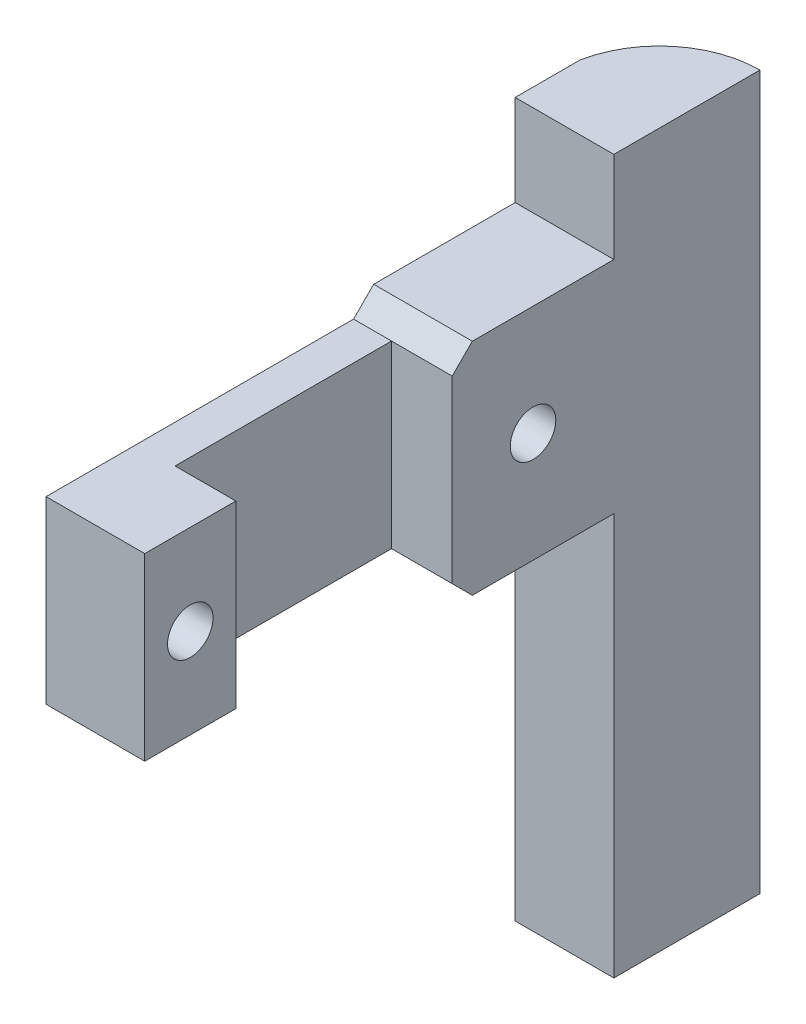
SolidWorks part; units mm, degrees
material "ABS"
ref_plane "Front" through (0, 0, 0) normal (0, 0, 1) x (1, 0, 0)
ref_plane "Top" through (0, 0, 0) normal (0, 1, 0) x (1, 0, 0)
ref_plane "Right" through (0, 0, 0) normal (1, 0, 0) x (0, 0, -1)
sketch "Sketch1" plane through (0, 0, 0) normal (1, 0, 0) x (0, 0, -1)
  line L1 (10.65, 14.5) -> (-10.65, 14.5)
  line L2 (10.65, 14.5) -> (10.65, -14.5)
  line L3 (10.65, -14.5) -> (-10.65, -14.5)
  line L4 (-10.65, 14.5) -> (-10.65, -14.5)
  line L5 (10.65, 14.5) -> (-10.65, -14.5) construction
  line L6 (10.65, -14.5) -> (-10.65, 14.5) construction
  point P0 (0, 0)
  dimension "D1" = 21.3
  dimension "D2" = 29
extrude "Boss-Extrude1" add sketch "Sketch1" along normal blind 25.87
sketch "Sketch3" plane through (25.87, 0, 0) normal (1, 0, 0) x (0, 0, -1)
  line L0 (-7.9983, 14.5) -> (-10.65, 11.8483)
  line L1 (-10.65, 11.8483) -> (-10.65, 14.5)
  line L2 (-10.65, 14.5) -> (-7.9983, 14.5)
  line L3 (-12.9395, 0) -> (4.891, 0)
  line L4 (10.65, 14.5) -> (-10.65, 14.5) construction
  line L5 (-10.65, 14.5) -> (-10.65, -14.5) construction
  line L6 (-10.65, -11.8483) -> (-10.65, -14.5)
  line L7 (-7.9983, -14.5) -> (-10.65, -11.8483)
  line L8 (-10.65, -14.5) -> (-7.9983, -14.5)
  line M6 (-10.65, 14.5) -> (-10.65, -14.5)
  line M7 (-10.65, -14.5) -> (10.65, -14.5)
  dimension "D1" = 0
  dimension "D2" = 45
  dimension "D3" = 3.75
  dimension "D4" = 17.8305
  dimension "D5" = 14.5
  dimension "D6" = 2.2895
extrude "Cut-Extrude1" cut sketch "Sketch3" against normal through all contours L7 M7 M6 | L1 L2 L0
sketch "Sketch5" plane through (0, 0, 10.65) normal (0, 0, 1) x (1, 0, 0)
  line L0 (25.87, 11.8483) -> (25.87, -11.8483) construction
  line L1 (25.87, 11.8483) -> (20.87, 11.8483)
  line L2 (25.87, 11.8483) -> (25.87, -11.8517)
  line L3 (25.87, -11.8517) -> (20.87, -11.8517)
  line L4 (20.87, 11.8483) -> (20.87, -11.8517)
  line L5 (25.87, 11.8483) -> (20.87, -11.8517) construction
  line L6 (25.87, -11.8517) -> (20.87, 11.8483) construction
  line L7 (5, 11.8483) -> (0, 11.8483)
  line L8 (5, 11.8483) -> (5, -11.8517)
  line L9 (5, -11.8517) -> (0, -11.8517)
  line L10 (0, 11.8483) -> (0, -11.8517)
  line L11 (5, 11.8483) -> (0, -11.8517) construction
  line L12 (5, -11.8517) -> (0, 11.8483) construction
  line L13 (0, 11.8483) -> (25.87, 11.8483) construction
  line L14 (0, 11.8483) -> (0, -11.8483) construction
  point P0 (23.37, -0.0017)
  point P5 (2.5, -0.0017)
  dimension "D1" = 0
  dimension "D2" = 5
  dimension "D3" = 0
  dimension "D4" = 23.7
  dimension "D5" = 0
  dimension "D6" = 0
  dimension "D7" = 5
  dimension "D8" = 23.7
extrude "Boss-Extrude2" add sketch "Sketch5" along normal blind 31.52
sketch "Sketch6" plane through (20.87, 0, 0) normal (-1, 0, 0) x (0, 0, 1)
  line L0 (42.17, 11.8483) -> (10.65, 11.8483) construction
  line L1 (42.17, 11.8483) -> (37.17, 11.8483)
  line L2 (42.17, 11.8483) -> (42.17, -11.8517)
  line L3 (42.17, -11.8517) -> (37.17, -11.8517)
  line L4 (37.17, 11.8483) -> (37.17, -11.8517)
  line L5 (42.17, 11.8483) -> (37.17, -11.8517) construction
  line L6 (42.17, -11.8517) -> (37.17, 11.8483) construction
  line L7 (42.17, 11.8483) -> (42.17, -11.8517) construction
  point P0 (39.67, -0.0017)
  point P5 (39.67, 11.8483)
  dimension "D1" = 0
  dimension "D2" = 0
  dimension "D3" = 5
  dimension "D4" = 23.7
extrude "Boss-Extrude3" add sketch "Sketch6" along normal blind 15.9
sketch "Sketch7" plane through (0, 0, -10.65) normal (0, 0, -1) x (-1, 0, 0)
  line L0 (-25.87, 14.5) -> (0, 14.5) construction
  line L1 (0, 26.5) -> (-25.87, 26.5)
  line L2 (0, 26.5) -> (0, -67.5)
  line L3 (0, -67.5) -> (-25.87, -67.5)
  line L4 (-25.87, 26.5) -> (-25.87, -67.5)
  line L5 (0, 26.5) -> (-25.87, -67.5) construction
  line L6 (0, -67.5) -> (-25.87, 26.5) construction
  line L7 (-25.87, -14.5) -> (0, -14.5) construction
  line L8 (0, -14.5) -> (0, 14.5) construction
  line L9 (-25.87, -14.5) -> (-25.87, 14.5) construction
  point P0 (-12.935, -20.5)
  point P5 (-12.935, 26.5)
  dimension "D1" = 12
  dimension "D2" = 53
  dimension "D3" = 0
  dimension "D4" = 0
extrude "Boss-Extrude4" add sketch "Sketch7" along normal blind 20
sketch "Sketch9" plane through (0, -67.5, 0) normal (0, -1, 0) x (-1, 0, 0)
  line L0 (-25.87, 10.65) -> (0, 10.65) construction
  line L1 (-25.87, 30.65) -> (-25.87, 10.65) construction
  line L2 (0.38, 16.65) -> (-26.12, 16.65)
  line L3 (-26.12, 16.65) -> (-26.12, 30.65)
  line L4 (-26.12, 30.65) -> (0.38, 30.65)
  line L5 (0.38, 30.65) -> (0.38, 16.65)
  circle A0 centre (-12.87, 16.65) radius 13.25
  line M5 (0, 10.65) -> (0, 30.65)
  line M6 (0, 30.65) -> (-25.87, 30.65)
  dimension "D1" = 6
  dimension "D2" = 13
  dimension "D3" = 26.5
  dimension "D4" = 14
  dimension "D5" = 26.5
  dimension "D6" = 90
extrude "Cut-Extrude2" cut sketch "Sketch9" against normal through all contours A0 L3 M5 M6
sketch "Sketch10" plane through (0, 0, 42.17) normal (0, 0, 1) x (1, 0, 0)
  line L1 (25.87, 11.8483) -> (0, 11.8483)
  line L2 (25.87, 11.8483) -> (25.87, -11.8517)
  line L3 (25.87, -11.8517) -> (0, -11.8517)
  line L4 (0, 11.8483) -> (0, -11.8517)
  dimension "D1" = 25.87
  dimension "D2" = 23.7
extrude "Boss-Extrude5" add sketch "Sketch10" along normal blind 9
sketch "Sketch13" plane through (0, 0, 51.17) normal (0, 0, 1) x (1, 0, 0)
  line L0 (0, 11.8483) -> (0, -11.8517) construction
  line L1 (12.87, 69.9983) -> (-12.87, 69.9983)
  line L2 (12.87, 69.9983) -> (12.87, -70.0017)
  line L3 (12.87, -70.0017) -> (-12.87, -70.0017)
  line L4 (-12.87, 69.9983) -> (-12.87, -70.0017)
  line L5 (12.87, 69.9983) -> (-12.87, -70.0017) construction
  line L6 (12.87, -70.0017) -> (-12.87, 69.9983) construction
  point P0 (0, -0.0017)
  dimension "D1" = 70
  dimension "D2" = 12.87
extrude "Cut-Extrude3" cut sketch "Sketch13" against normal through all
mirror "Mirror2" about plane through (12.87, 69.9983, -29.9) normal (1, 0, 0) of "Cut-Extrude3", "Cut-Extrude1", "Boss-Extrude2", "Boss-Extrude5", "Cut-Extrude2", "Boss-Extrude1", "Boss-Extrude4"
sketch "Sketch14" plane through (4.87, 0, 0) normal (1, 0, 0) x (0, 0, -1)
  line L0 (-42.17, 11.8483) -> (-10.65, 11.8483) construction
  line L1 (-46.17, 11.8483) -> (-39.17, 11.8483)
  line L2 (-46.17, 11.8483) -> (-46.17, -11.8517)
  line L3 (-46.17, -11.8517) -> (-39.17, -11.8517)
  line L4 (-39.17, 11.8483) -> (-39.17, -11.8517)
  line L6 (-10.65, 11.8483) -> (-10.65, -11.8483) construction
  dimension "D1" = 7
  dimension "D2" = 23.7
  dimension "D3" = 0
  dimension "D4" = 35.52
extrude "Boss-Extrude6" add sketch "Sketch14" along normal blind 8
hole_wizard "Ø6.0mm Clearance Dowel Hole1" positions "Sketch15" profile "Sketch16" hole size "Ø6.0" standard "ANSI Metric" end condition through all
sketch "Sketch15" plane through (12.87, 0, 0) normal (1, 0, 0) x (0, 0, -1)
  line L0 (-39.17, 11.8483) -> (-51.17, 11.8483) construction
  line L1 (-39.17, -11.8517) -> (-39.17, 11.8483) construction
  point P0 (-45.17, 0)
  point P2 (0, 0)
  dimension "D1" = 11.8483
  dimension "D2" = 6
sketch "Sketch16" plane through (12.87, 0, 45.17) normal (0, 1, 0) x (0, 0, -1)
  line L0 (0, 0) -> (0, 13)
  line L1 (0, 13) -> (3, 13)
  line L2 (3, 13) -> (3, 0)
  line L5 (3, 0) -> (0, 0)
  line L11 (0, -6.35) -> (0, 107.95) construction
  dimension "Thru Hole Dia." = 6
  dimension "Thru Hole Depth" = 13
